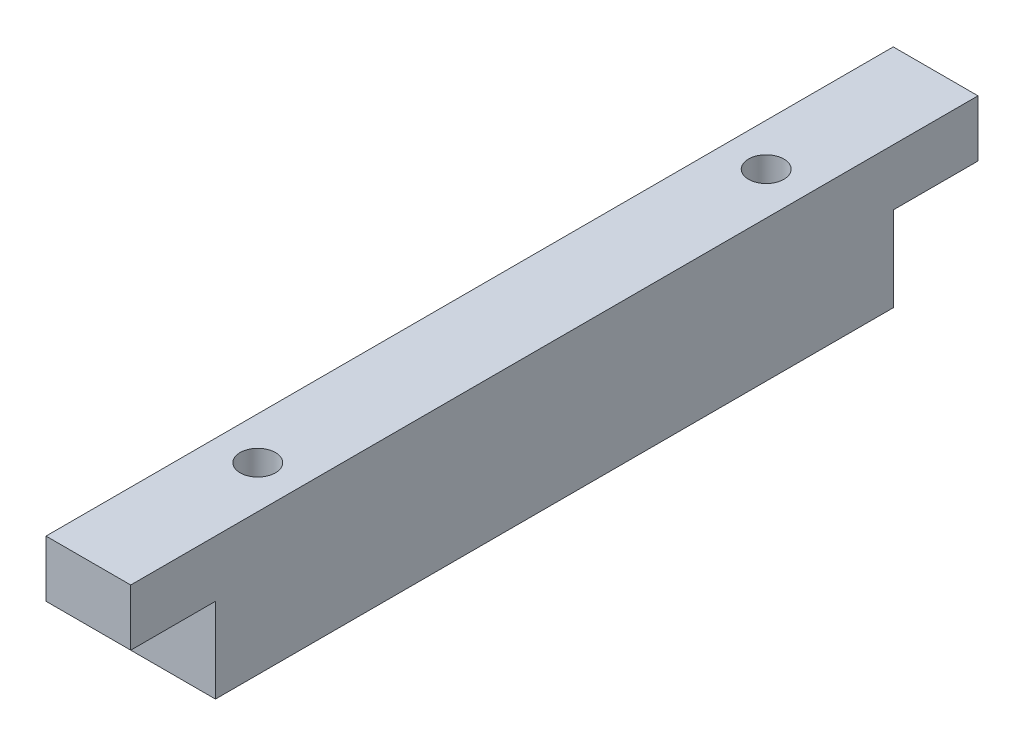
SolidWorks part; units mm, degrees
material "ABS"
ref_plane "Front Plane" through (0, 0, 0) normal (0, 0, 1) x (1, 0, 0)
ref_plane "Top Plane" through (0, 0, 0) normal (0, 1, 0) x (1, 0, 0)
ref_plane "Right Plane" through (0, 0, 0) normal (1, 0, 0) x (0, 0, -1)
sketch "Sketch1" plane through (0, 0, 0) normal (1, 0, 0) x (0, 0, -1)
  line L0 (0, 6) -> (0, 10)
  line L1 (0, 10) -> (60, 10)
  line L2 (60, 10) -> (60, 6)
  line L3 (60, 6) -> (54, 6)
  line L4 (54, 6) -> (54, 0)
  line L5 (54, 0) -> (6, 0)
  line L6 (6, 0) -> (6, 6)
  line L7 (6, 6) -> (0, 6)
  dimension "D1" = 6
  dimension "D2" = 6
  dimension "D3" = 10
  dimension "D4" = 60
  dimension "D5" = 6
extrude "Boss-Extrude1" add sketch "Sketch1" along normal blind 6
hole_wizard "Tap Drill for M3x0.5 Tap1" positions "Sketch3" profile "Sketch2" hole size "M3x0.5" standard "ANSI Metric" end condition up to next
sketch "Sketch3" plane through (0, 0, 0) normal (0, -1, 0) x (-1, 0, 0)
  line L2 (0, 6) -> (0, 54) construction
  line L3 (-6, 54) -> (0, 54) construction
  line L4 (-6, 6) -> (0, 6) construction
  point P0 (-3, 12)
  point P2 (-3, 48)
  dimension "D1" = 6
  dimension "D2" = 6
  dimension "D3" = 3
sketch "Sketch2" plane through (3, 0, -12) normal (1, 0, 0) x (0, 0, -1)
  line L0 (0, 0) -> (0, 10)
  line L1 (0, 10) -> (1.25, 10)
  line L2 (1.25, 10) -> (1.25, 0)
  line L5 (1.25, 0) -> (0, 0)
  line L11 (0, -6.35) -> (0, 107.95) construction
  dimension "Thru Hole Dia." = 2.5
  dimension "Thru Hole Depth" = 10
